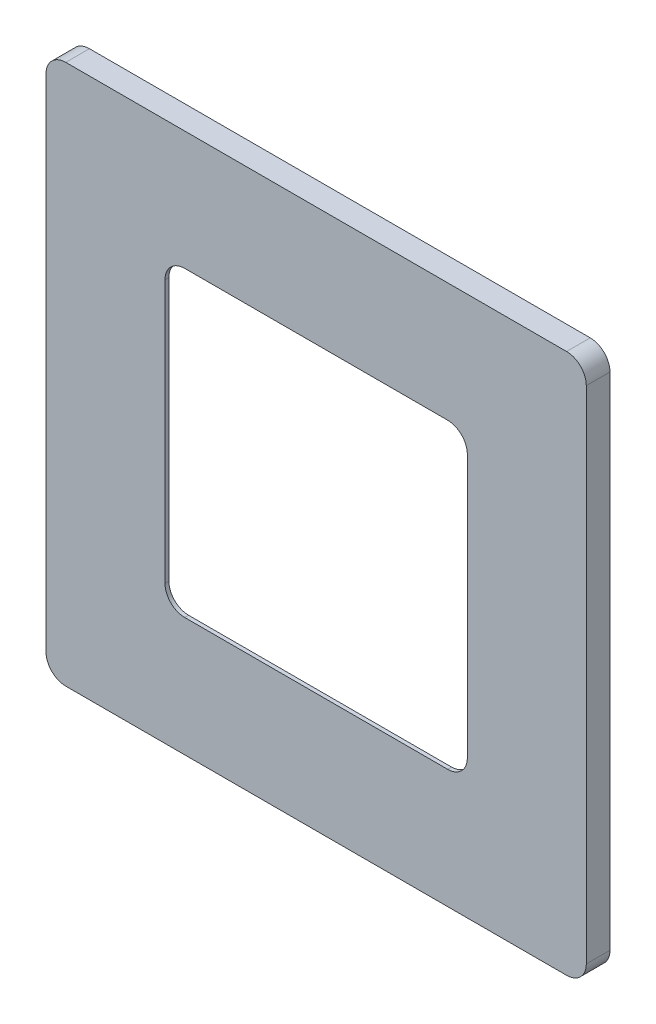
SolidWorks part; units mm, degrees
ref_plane "Front Plane" through (0, 0, 0) normal (0, 0, 1) x (1, 0, 0)
ref_plane "Top Plane" through (0, 0, 0) normal (0, 1, 0) x (1, 0, 0)
ref_plane "Right Plane" through (0, 0, 0) normal (1, 0, 0) x (0, 0, -1)
sketch "Sketch1" plane through (0, 0, 0) normal (0, 1, 0) x (1, 0, 0)
  line L1 (41.1, 3.6) -> (-41.1, 3.6)
  line L2 (41.1, 3.6) -> (41.1, 0)
  line L3 (-41.1, 3.6) -> (-41.1, 0)
  line L5 (0, -1.941) -> (0, 24.0569) construction
  line L9 (-41.1, 0) -> (41.1, 0)
  point P19 (0, 0)
  dimension "D2" = 82.2
  dimension "D5" = 3.6
extrude "Boss-Extrude1" add sketch "Sketch1" along normal blind 82.2
ref_plane "Plane1" through (0, 0, -3.6) normal (0, 0, -1) x (-1, 0, 0)
sketch "Sketch2" plane through (0, 0, -3.6) normal (0, 0, -1) x (-1, 0, 0)
  line L0 (0, 1.98) -> (0, -1.98) construction
  line L1 (38.2, 2.9) -> (-38.2, 2.9)
  line L2 (38.2, 2.9) -> (38.2, 79.3)
  line L3 (38.2, 79.3) -> (-38.2, 79.3)
  line L4 (-38.2, 2.9) -> (-38.2, 79.3)
  line L5 (38.2, 2.9) -> (-38.2, 79.3) construction
  line L6 (38.2, 79.3) -> (-38.2, 2.9) construction
  line L7 (0, 0) -> (0, 82.2) construction
  line L8 (-41.1, 82.2) -> (41.1, 82.2) construction
  point P0 (0, 41.1)
  point P13 (0, 41.1)
  dimension "D1" = 76.4
extrude "Cut-Extrude1" cut sketch "Sketch2" against normal blind 1.31
sketch "Sketch4" plane through (0, 0, -3.6) normal (0, 0, -1) x (-1, 0, 0)
  circle A0 centre (38.2, 2.9) radius 1
  circle A1 centre (38.2, 79.3) radius 1
  circle A2 centre (-38.2, 2.9) radius 1
  circle A3 centre (-38.2, 79.3) radius 1
  dimension "D1" = 2
extrude "Cut-Extrude3" cut sketch "Sketch4" against normal up to surface (1.31 mm away) up to face at (0, 41.1, -2.29)
sketch "Sketch3" plane through (0, 0, -2.29) normal (0, 0, -1) x (-1, 0, 0)
  line L1 (23, 18.1) -> (-23, 18.1)
  line L2 (23, 18.1) -> (23, 64.1)
  line L3 (23, 64.1) -> (-23, 64.1)
  line L4 (-23, 18.1) -> (-23, 64.1)
  line L5 (23, 18.1) -> (-23, 64.1) construction
  line L6 (23, 64.1) -> (-23, 18.1) construction
  point P0 (0, 41.1)
  dimension "D1" = 46
extrude "Cut-Extrude2" cut sketch "Sketch3" against normal through all
sketch "Sketch6" plane through (0, 0, -2.29) normal (0, 0, 1) x (1, 0, 0)
  line L0 (-41.1, 82.2) -> (41.1, 0) construction
  line L1 (-25.15, 66.25) -> (25.15, 66.25)
  line L2 (-25.15, 66.25) -> (-25.15, 15.95)
  line L3 (-25.15, 15.95) -> (25.15, 15.95)
  line L4 (25.15, 66.25) -> (25.15, 15.95)
  line L5 (-25.15, 15.95) -> (25.15, 66.25) construction
  point P8 (0, 41.1)
  dimension "D1" = 50.3
extrude "Cut-Extrude4" cut sketch "Sketch6" along normal blind 1.7
fillet "Fillet1" radius 3 8 edges at (-23, 64.1, -0.295) (23, 64.1, -0.295) (23, 18.1, -0.295) (-23, 18.1, -0.295) (41.1, 0, -1.8) (-41.1, 0, -1.8) (-41.1, 82.2, -1.8) (41.1, 82.2, -1.8)
fillet "Fillet2" radius 2 8 edges at (37.2, 2.9, -2.945) (38.2, 3.9, -2.945) (38.2, 78.3, -2.945) (37.2, 79.3, -2.945) (-37.2, 79.3, -2.945) (-38.2, 78.3, -2.945) (-38.2, 3.9, -2.945) (-37.2, 2.9, -2.945)
